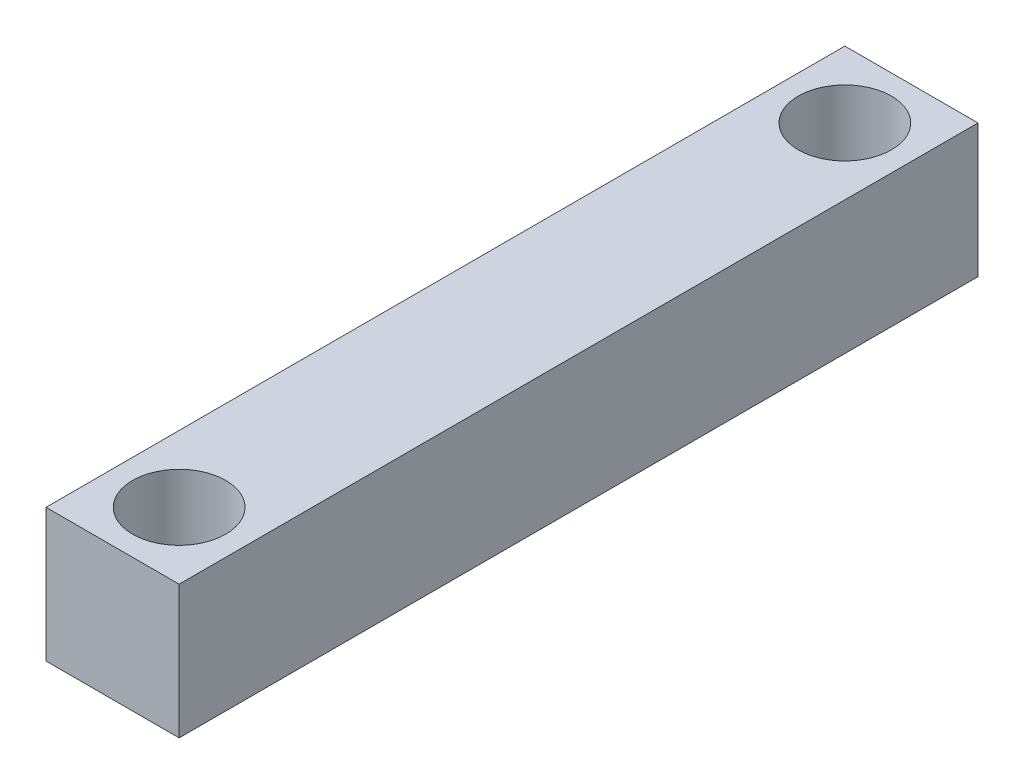
SolidWorks part; units mm, degrees
ref_plane "Piano frontale" through (0, 0, 0) normal (0, 0, 1) x (1, 0, 0)
ref_plane "Piano superiore" through (0, 0, 0) normal (0, 1, 0) x (1, 0, 0)
ref_plane "Piano destro" through (0, 0, 0) normal (1, 0, 0) x (0, 0, -1)
sketch "Schizzo1" plane through (0, 0, 0) normal (0, 0, 1) x (1, 0, 0)
  line L0 (0, 0) -> (-5, 0)
  line L1 (-5, 0) -> (-5, 5)
  line L2 (-5, 5) -> (0, 5)
  line L3 (0, 5) -> (0, 0)
  dimension "D1" = 5
extrude "Estrusione-Estrusione1" add sketch "Schizzo1" along normal blind 30
sketch "Schizzo2" plane through (0, 0, 0) normal (0, -1, 0) x (-1, 0, 0)
  line L0 (5, 0) -> (0, 0) construction
  line L1 (2.5, -30) -> (2.5, 3.3709) construction
  line L2 (5, -30) -> (0, -30) construction
  circle A0 centre (2.5, -27.5) radius 1.75
  circle A1 centre (2.5, -2.5) radius 1.75
  dimension "D3" = 3.5
  dimension "D1" = 25
  dimension "D2" = 2.5
extrude "Taglio-Estrusione1" cut sketch "Schizzo2" against normal through all
